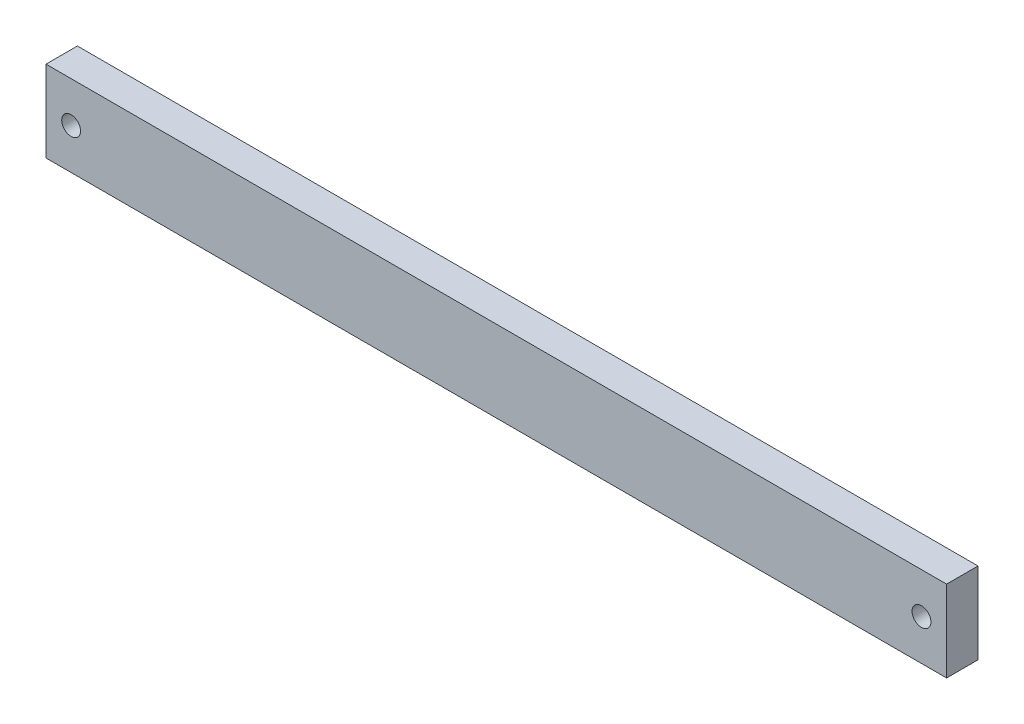
SolidWorks part; units mm, degrees
ref_plane "Front Plane" through (0, 0, 0) normal (0, 0, 1) x (1, 0, 0)
ref_plane "Top Plane" through (0, 0, 0) normal (0, 1, 0) x (1, 0, 0)
ref_plane "Right Plane" through (0, 0, 0) normal (1, 0, 0) x (0, 0, -1)
sketch "Sketch1" plane through (0, 0, 0) normal (0, 0, 1) x (1, 0, 0)
  line L0 (-554.918, 0) -> (599.3115, 0) construction
  line L1 (0, 310.7541) -> (0, -358.847) construction
  line L3 (-358.5, 32.3702) -> (358.5, 32.3702)
  line L4 (-358.5, 32.3702) -> (-358.5, -32.3702)
  line L5 (-358.5, -32.3702) -> (358.5, -32.3702)
  line L6 (358.5, 32.3702) -> (358.5, -32.3702)
  line L7 (-358.5, 32.3702) -> (358.5, -32.3702) construction
  line L8 (-358.5, -32.3702) -> (358.5, 32.3702) construction
  point P5 (0, 0)
  dimension "D1" = 717
extrude "Boss-Extrude1" add sketch "Sketch1" along normal blind 25
sketch "Sketch2" plane through (0, 0, 0) normal (0, 0, -1) x (-1, 0, 0)
  circle A0 centre (-338.5, 0) radius 7.5
  circle A1 centre (338.5, 0) radius 7.5
  dimension "D1" = 15
  dimension "D2" = 15
  dimension "D3" = 338.5
  dimension "D4" = 338.5
extrude "Cut-Extrude1" cut sketch "Sketch2" against normal through all both and the other way through all
